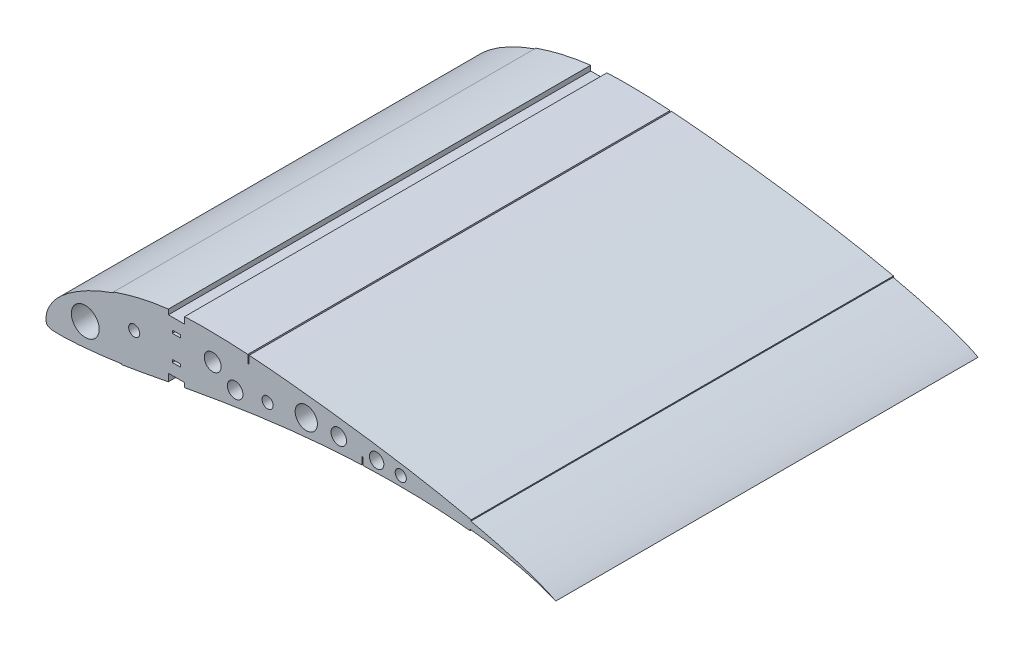
SolidWorks part; units mm, degrees
ref_plane "Front" through (0, 0, 0) normal (0, 0, 1) x (1, 0, 0)
ref_plane "Top" through (0, 0, 0) normal (0, 1, 0) x (1, 0, 0)
ref_plane "Right" through (0, 0, 0) normal (1, 0, 0) x (0, 0, -1)
curve "s1223bot"
  spline degree 3 poles (0.0013, 0.0452, 0) (0.0011, -0.0169, 0) (0.0007, -0.1295, 0) (0.0502, -0.2994, 0) (0.2271, -0.3838, 0) (0.4658, -0.3956, 0) (0.7919, -0.4071, 0) (1.2021, -0.3894, 0) (1.6917, -0.3569, 0) (2.2553, -0.3048, 0) (2.887, -0.2344, 0) (3.5838, -0.144, 0) (4.3454, -0.0178, 0) (5.1754, 0.1406, 0) (6.078, 0.3129, 0) (7.0488, 0.4949, 0) (8.0817, 0.6789, 0) (9.1691, 0.8581, 0) (10.3026, 1.0265, 0) (11.4724, 1.1779, 0) (12.668, 1.3079, 0) (13.8781, 1.4106, 0) (15.0905, 1.4835, 0) (16.2926, 1.5235, 0) (17.4713, 1.5286, 0) (18.6136, 1.4983, 0) (19.7062, 1.4334, 0) (20.7362, 1.3347, 0) (21.691, 1.2061, 0) (22.5587, 1.0511, 0) (23.3281, 0.8754, 0) (23.9878, 0.686, 0) (24.5221, 0.4881, 0) (24.9172, 0.2964, 0) (25.1776, 0.1426, 0) (25.3238, 0.0503, 0) (25.3852, 0.0098, 0) (25.4, 0, 0) knots 0 0 0 0 0.00721 0.013063 0.018988 0.028118 0.040671 0.056473 0.075356 0.097133 0.121591 0.148499 0.177977 0.210404 0.245731 0.28372 0.324063 0.36646 0.410535 0.455921 0.502185 0.548913 0.595655 0.641938 0.687301 0.731277 0.773403 0.813231 0.85031 0.884246 0.914623 0.941088 0.963171 0.980104 0.991535 0.99796 1 1 1 1
curve "s1223top"
  spline degree 3 poles (25.4, 0, 0) (25.3862, 0.0106, 0) (25.3348, 0.0499, 0) (25.2363, 0.1391, 0) (25.0929, 0.2743, 0) (24.903, 0.4317, 0) (24.6516, 0.5857, 0) (24.3364, 0.7365, 0) (23.9567, 0.8934, 0) (23.5122, 1.0548, 0) (23.0051, 1.2193, 0) (22.4381, 1.3857, 0) (21.8144, 1.5531, 0) (21.1374, 1.72, 0) (20.4109, 1.8852, 0) (19.6393, 2.0477, 0) (18.8274, 2.2065, 0) (17.9798, 2.3598, 0) (17.102, 2.5074, 0) (16.1989, 2.6472, 0) (15.2763, 2.7797, 0) (14.3403, 2.9038, 0) (13.3976, 3.019, 0) (12.4558, 3.1262, 0) (11.5225, 3.2227, 0) (10.6055, 3.3067, 0) (9.7111, 3.3734, 0) (8.8446, 3.4193, 0) (8.0106, 3.4391, 0) (7.2135, 3.437, 0) (6.4548, 3.3979, 0) (5.7342, 3.3188, 0) (5.0487, 3.207, 0) (4.3982, 3.0621, 0) (3.7833, 2.8923, 0) (3.2067, 2.7004, 0) (2.6707, 2.491, 0) (2.1788, 2.2652, 0) (1.7325, 2.0276, 0) (1.3343, 1.7809, 0) (0.9865, 1.5284, 0) (0.6894, 1.2755, 0) (0.4475, 1.0194, 0) (0.2611, 0.7624, 0) (0.125, 0.5124, 0) (0.0331, 0.275, 0) (0.0114, 0.1182, 0) (0.0013, 0.0452, 0) knots 0 0 0 0 0.001921 0.007154 0.014672 0.023714 0.034361 0.047156 0.062314 0.079753 0.099423 0.121231 0.145064 0.170804 0.198305 0.227412 0.257958 0.289755 0.322619 0.356355 0.390772 0.425638 0.460723 0.495752 0.530423 0.564432 0.59754 0.629553 0.660343 0.689741 0.717642 0.744276 0.769837 0.794379 0.817909 0.840322 0.861527 0.881481 0.900118 0.917382 0.933225 0.947578 0.96045 0.972074 0.982556 0.991876 1 1 1 1
ref_plane "Plane1" through (0, 0, 0) normal (0, 0, 1) x (1, 0, 0)
sketch "Sketch1" plane through (0, 0, 0) normal (0, 0, 1) x (1, 0, 0)
  line L0 (0.03, 1.0671) -> (599.47, 0) construction
  spline S2 degree 3 poles (0.03, 1.0671) (0.0255, -0.3992) (0.0173, -3.0557) (1.1853, -7.0667) (5.3593, -9.0582) (10.9923, -9.3375) (18.689, -9.6083) (28.3716, -9.1908) (39.9268, -8.4236) (53.2273, -7.1946) (68.1365, -5.5318) (84.582, -3.3994) (102.5555, -0.4191) (122.1448, 3.3182) (143.4476, 7.3855) (166.3598, 11.68) (190.7376, 16.0235) (216.4019, 20.2529) (243.1537, 24.227) (270.7622, 27.8) (298.9794, 30.8679) (327.5386, 33.293) (356.1532, 35.012) (384.5243, 35.9571) (412.3442, 36.0765) (439.3023, 35.362) (465.0901, 33.8306) (489.3978, 31.5015) (511.9341, 28.4655) (532.4122, 24.8063) (550.5712, 20.6608) (566.1399, 16.1904) (578.7504, 11.5186) (588.0748, 6.9961) (594.2214, 3.3662) (597.6712, 1.1861) (599.1206, 0.2303) (599.47, 0) knots 0 0 0 0 0.00721 0.013063 0.018988 0.028118 0.040671 0.056473 0.075356 0.097133 0.121591 0.148499 0.177977 0.210404 0.245731 0.28372 0.324063 0.36646 0.410535 0.455921 0.502185 0.548913 0.595655 0.641938 0.687301 0.731277 0.773403 0.813231 0.85031 0.884246 0.914623 0.941088 0.963171 0.980104 0.991535 0.99796 1 1 1 1
  spline S3 degree 3 poles (599.47, 0) (599.1444, 0.2495) (597.9316, 1.1785) (595.6059, 3.2827) (592.2219, 6.473) (587.7401, 10.189) (581.8079, 13.8236) (574.3676, 17.3833) (565.407, 21.0846) (554.9146, 24.8937) (542.9479, 28.7777) (529.5663, 32.7048) (514.8456, 36.6559) (498.8667, 40.5951) (481.7214, 44.4936) (463.5118, 48.3272) (444.3491, 52.0761) (424.3454, 55.6943) (403.6266, 59.1765) (382.3121, 62.4779) (360.5397, 65.605) (338.449, 68.533) (316.1999, 71.2524) (293.9704, 73.7827) (271.9445, 76.0598) (250.3016, 78.0413) (229.194, 79.6155) (208.7421, 80.6984) (189.0598, 81.166) (170.248, 81.1163) (152.3416, 80.1952) (135.3339, 78.3286) (119.1554, 75.6893) (103.8024, 72.2701) (89.2906, 68.2606) (75.6814, 63.7319) (63.0327, 58.7898) (51.4231, 53.4607) (40.8898, 47.853) (31.49, 42.0304) (23.2831, 36.0717) (16.2711, 30.1033) (10.5604, 24.0601) (6.1626, 17.9941) (2.9495, 12.0933) (0.782, 6.4892) (0.2689, 2.7899) (0.03, 1.0671) knots 0 0 0 0 0.001921 0.007154 0.014672 0.023714 0.034361 0.047156 0.062314 0.079753 0.099423 0.121231 0.145064 0.170804 0.198305 0.227412 0.257958 0.289755 0.322619 0.356355 0.390772 0.425638 0.460723 0.495752 0.530423 0.564432 0.59754 0.629553 0.660343 0.689741 0.717642 0.744276 0.769837 0.794379 0.817909 0.840322 0.861527 0.881481 0.900118 0.917382 0.933225 0.947578 0.96045 0.972074 0.982556 0.991876 1 1 1 1
  dimension "D1" = 599.44
extrude "Boss-Extrude1" add sketch "Sketch1" along normal blind 482.6
sketch "Sketch2" plane through (0, 0, 0) normal (0, 0, -1) x (-1, 0, 0)
  line L0 (0, 0) -> (-599.47, 0) construction
  line L1 (-149.86, 0) -> (-149.86, 151.2393) construction
  line L2 (-149.86, 44.2563) -> (-84.0346, 44.2563) construction
  line L3 (-149.86, 79.8163) -> (-80.7882, 79.8163) construction
  line L4 (-145.0975, 31.3975) -> (-145.0975, 28.2225)
  line L5 (-154.6225, 57.115) -> (-145.0975, 57.115)
  line L6 (-154.6225, 57.115) -> (-154.6225, 60.29)
  line L7 (-154.6225, 60.29) -> (-145.0975, 60.29)
  line L8 (-145.0975, 57.115) -> (-145.0975, 60.29)
  line L9 (-154.6225, 57.115) -> (-145.0975, 60.29) construction
  line L10 (-154.6225, 60.29) -> (-145.0975, 57.115) construction
  line L11 (-159.0675, 73.1488) -> (-140.6525, 73.1488)
  line L12 (-159.0675, 73.1488) -> (-159.0675, 89.0044)
  line L13 (-159.0675, 89.0044) -> (-140.6525, 89.0044)
  line L14 (-140.6525, 73.1488) -> (-140.6525, 89.0044)
  line L15 (-159.0675, 73.1488) -> (-140.6525, 89.0044) construction
  line L16 (-159.0675, 89.0044) -> (-140.6525, 73.1488) construction
  line L17 (-154.6225, 28.2225) -> (-145.0975, 28.2225)
  line L18 (-154.6225, 31.3975) -> (-154.6225, 28.2225)
  line L19 (-154.6225, 31.3975) -> (-145.0975, 31.3975)
  line L20 (-159.0675, -0.4918) -> (-140.6525, -0.4918)
  line L21 (-140.6525, 15.3638) -> (-140.6525, -0.4918)
  line L22 (-159.0675, 15.3638) -> (-140.6525, 15.3638)
  line L23 (-159.0675, 15.3638) -> (-159.0675, -0.4918)
  line L25 (-231.3937, 96.4856) -> (-232.9812, 96.4856)
  line L26 (-231.3937, 96.4856) -> (-231.3937, 70.3014)
  line L27 (-231.3937, 70.3014) -> (-232.9812, 70.3014)
  line L28 (-232.9812, 96.4856) -> (-232.9812, 70.3014)
  line L29 (-231.3937, 96.4856) -> (-232.9812, 70.3014) construction
  line L31 (-361.6917, 26.0584) -> (-363.2792, 26.0584)
  line L32 (-361.6917, 26.0584) -> (-361.6917, 43.6863)
  line L33 (-361.6917, 43.6863) -> (-363.2792, 43.6863)
  line L34 (-363.2792, 26.0584) -> (-363.2792, 43.6863)
  line L35 (-361.6917, 26.0584) -> (-363.2792, 43.6863) construction
  line L36 (-361.6917, 43.6863) -> (-363.2792, 26.0584) construction
  circle A2 centre (-45.7138, 19.2098) radius 15.9068
  spline S0 degree 3 poles (-599.47, 0) (-599.1444, 0.2495) (-597.9316, 1.1785) (-595.6059, 3.2827) (-592.2219, 6.473) (-587.7401, 10.189) (-581.8079, 13.8236) (-574.3676, 17.3833) (-565.407, 21.0846) (-554.9146, 24.8937) (-542.9479, 28.7777) (-529.5663, 32.7048) (-514.8456, 36.6559) (-498.8667, 40.5951) (-481.7214, 44.4936) (-463.5118, 48.3272) (-444.3491, 52.0761) (-424.3454, 55.6943) (-403.6266, 59.1765) (-382.3121, 62.4779) (-360.5397, 65.605) (-338.449, 68.533) (-316.1999, 71.2524) (-293.9704, 73.7827) (-271.9445, 76.0598) (-250.3016, 78.0413) (-229.194, 79.6155) (-208.7421, 80.6984) (-189.0598, 81.166) (-170.248, 81.1163) (-152.3416, 80.1952) (-135.3339, 78.3286) (-119.1554, 75.6893) (-103.8024, 72.2701) (-89.2906, 68.2606) (-75.6814, 63.7319) (-63.0327, 58.7898) (-51.4231, 53.4607) (-40.8898, 47.853) (-31.49, 42.0304) (-23.2831, 36.0717) (-16.2711, 30.1033) (-10.5604, 24.0601) (-6.1626, 17.9941) (-2.9495, 12.0933) (-0.782, 6.4892) (-0.2689, 2.7899) (-0.03, 1.0671) knots 0 0 0 0 0.001921 0.007154 0.014672 0.023714 0.034361 0.047156 0.062314 0.079753 0.099423 0.121231 0.145064 0.170804 0.198305 0.227412 0.257958 0.289755 0.322619 0.356355 0.390772 0.425638 0.460723 0.495752 0.530423 0.564432 0.59754 0.629553 0.660343 0.689741 0.717642 0.744276 0.769837 0.794379 0.817909 0.840322 0.861527 0.881481 0.900118 0.917382 0.933225 0.947578 0.96045 0.972074 0.982556 0.991876 1 1 1 1 construction
  point P7 (-149.86, 58.7025)
  point P17 (-149.86, 81.0766)
  point P39 (-362.4855, 34.8724)
  dimension "D8" = 31.8135
  dimension "D1" = 149.86
  dimension "D2" = 35.56
  dimension "D3" = 14.4462
  dimension "D4" = 9.525
  dimension "D5" = 3.175
  dimension "D6" = 18.415
  dimension "D7" = 28.8925
  dimension "D10" = 1.5875
  dimension "D11" = 1.5875
extrude "Cut-Extrude1" cut sketch "Sketch2" against normal through all
sketch "Sketch3" plane through (0, 0, 482.6) normal (0, 0, 1) x (1, 0, 0)
  line L0 (77.9334, 64.4077) -> (87.0074, -2.931) construction
  line L1 (77.9334, 64.4077) -> (78.1966, 63.6589)
  line L2 (87.0074, -2.931) -> (86.8874, -2.1464)
  line L3 (486.6728, 43.3483) -> (485.4189, 31.7937) construction
  line L4 (485.4189, 31.7937) -> (485.5901, 33.372)
  line L5 (486.6728, 43.3483) -> (486.3262, 41.799)
  spline S0 degree 3 poles (-1970.3924, 338.6511) (98.8632, 45.6756) (-8.8415, 27.3664) (1.1853, -7.0667) (5.3593, -9.0582) (10.9923, -9.3375) (18.689, -9.6083) (28.3716, -9.1908) (39.9268, -8.4236) (53.2273, -7.1946) (68.1365, -5.5318) (84.582, -3.3994) (102.5555, -0.4191) (473.5396, 70.358) (838.1335, 141.3605) (1502.5551, -1332.6043) knots -0.144018 -0.144018 -0.144018 -0.144018 0.00721 0.013063 0.018988 0.028118 0.040671 0.056473 0.075356 0.097133 0.121591 0.148499 0.177977 0.210404 1.989908 1.989908 1.989908 1.989908 only from (0.03, 1.0671) to (140.6525, 6.8433) construction
  spline S1 degree 3 poles (277.129, -1844.3223) (714.082, -186.0597) (395.3013, 120.739) (119.1554, 75.6893) (103.8024, 72.2701) (89.2906, 68.2606) (75.6814, 63.7319) (63.0327, 58.7898) (51.4231, 53.4607) (40.8898, 47.853) (31.49, 42.0304) (23.2831, 36.0717) (16.2711, 30.1033) (10.5604, 24.0601) (6.1626, 17.9941) (2.9495, 12.0933) (-13.1155, -29.4414) (78.3319, -94.0823) (-1968.3105, 348.48) knots -0.515421 -0.515421 -0.515421 -0.515421 0.744276 0.769837 0.794379 0.817909 0.840322 0.861527 0.881481 0.900118 0.917382 0.933225 0.947578 0.96045 0.972074 0.982556 0.991876 1.179048 1.179048 1.179048 1.179048 only from (140.6525, 78.86) to (0.03, 1.0671) construction
  spline S2 degree 3 poles (0.03, 1.0671) (0.0255, -0.3992) (0.0173, -3.0557) (1.1853, -7.0667) (5.3593, -9.0582) (10.9923, -9.3375) (18.689, -9.6083) (28.3716, -9.1908) (39.9268, -8.4236) (53.2273, -7.1946) (68.1365, -5.5318) (79.5756, -4.0486) (86.0206, -3.0819) (87.0074, -2.931) knots 0 0 0 0 0.00721 0.013063 0.018988 0.028118 0.040671 0.056473 0.075356 0.097133 0.121591 0.148499 0.153366 0.153366 0.153366 0.153366
  spline S3 degree 3 poles (77.9334, 64.4077) (77.114, 64.1196) (72.0313, 62.3057) (63.0327, 58.7898) (51.4231, 53.4607) (40.8898, 47.853) (31.49, 42.0304) (23.2831, 36.0717) (16.2711, 30.1033) (10.5604, 24.0601) (6.1626, 17.9941) (2.9495, 12.0933) (0.782, 6.4892) (0.2689, 2.7899) (0.03, 1.0671) knots 0.836254 0.836254 0.836254 0.836254 0.840322 0.861527 0.881481 0.900118 0.917382 0.933225 0.947578 0.96045 0.972074 0.982556 0.991876 1 1 1 1
  spline S4 degree 1 poles (78.1966, 63.6589) (0.8236, 1.0111) knots 0 0 1 1 construction
  spline S5 degree 1 poles (0.8236, 1.0111) (86.8874, -2.1464) knots 0 0 1 1 construction
  spline S6 degree 3 poles (78.1966, 63.6589) (69.9856, 60.7723) (57.8565, 55.8468) (42.3943, 47.8342) (31.2745, 41.0045) (22.5488, 34.51) (16.0869, 28.7338) (11.6338, 24.0169) (7.7076, 18.8608) (4.9669, 14.2264) (3.1357, 10.321) (1.9971, 7.3155) (1.2705, 4.2499) (0.9722, 2.0827) (0.8236, 1.0111) knots 0.836254 0.836254 0.836254 0.836254 0.87717 0.897628 0.918086 0.938543 0.948772 0.959001 0.96923 0.979459 0.984573 0.989688 0.994802 0.999917 0.999917 0.999917 0.999917
  spline S7 degree 3 poles (0.8236, 1.0111) (0.8221, 0.5289) (0.8199, -0.4416) (0.8716, -1.8611) (1.0281, -3.2766) (1.3362, -4.6703) (1.8567, -5.8585) (2.8808, -6.9975) (5.0911, -7.9582) (7.8516, -8.3986) (11.7354, -8.5583) (16.6431, -8.7442) (22.4904, -8.6592) (28.3666, -8.3658) (34.2408, -8.0058) (40.109, -7.5703) (45.9731, -7.0649) (53.7874, -6.3127) (63.5446, -5.2532) (75.2379, -3.8289) (83.0086, -2.7395) (86.8874, -2.1464) knots 0.000088 0.000088 0.000088 0.000088 0.002483 0.004878 0.007273 0.009668 0.012063 0.014458 0.019248 0.024037 0.028827 0.038407 0.047987 0.057567 0.067147 0.076727 0.086307 0.095887 0.115046 0.134206 0.153366 0.153366 0.153366 0.153366
  spline S8 degree 3 poles (-583.8836, 1359.92) (-752.4483, -493.2907) (-179.6719, 33.5361) (412.3442, 36.0765) (439.3023, 35.362) (465.0901, 33.8306) (489.3978, 31.5015) (511.9341, 28.4655) (532.4122, 24.8063) (550.5712, 20.6608) (566.1399, 16.1904) (578.7504, 11.5186) (588.0748, 6.9961) (594.2214, 3.3662) (633.3139, -21.3389) (658.727, -62.7912) (1792.2745, 1603.3571) knots -2.154817 -2.154817 -2.154817 -2.154817 0.641938 0.687301 0.731277 0.773403 0.813231 0.85031 0.884246 0.914623 0.941088 0.963171 0.980104 0.991535 0.99796 1.205564 1.205564 1.205564 1.205564 only from (363.2792, 35.1934) to (599.47, 0) construction
  spline S9 degree 3 poles (-603.0561, -1596.942) (659.4194, -4.3542) (616.3736, -15.5063) (595.6059, 3.2827) (592.2219, 6.473) (587.7401, 10.189) (581.8079, 13.8236) (574.3676, 17.3833) (565.407, 21.0846) (554.9146, 24.8937) (542.9479, 28.7777) (529.5663, 32.7048) (514.8456, 36.6559) (498.8667, 40.5951) (481.7214, 44.4936) (463.5118, 48.3272) (444.3491, 52.0761) (424.3454, 55.6943) (403.6266, 59.1765) (382.3121, 62.4779) (360.5397, 65.605) (338.449, 68.533) (316.1999, 71.2524) (293.9704, 73.7827) (271.9445, 76.0598) (-43.152, 104.9077) (-360.3028, 21.1709) (-697.8307, -1621.5504) knots -0.116345 -0.116345 -0.116345 -0.116345 0.001921 0.007154 0.014672 0.023714 0.034361 0.047156 0.062314 0.079753 0.099423 0.121231 0.145064 0.170804 0.198305 0.227412 0.257958 0.289755 0.322619 0.356355 0.390772 0.425638 0.460723 0.495752 0.530423 0.564432 1.97767 1.97767 1.97767 1.97767 only from (599.47, 0) to (232.9812, 79.2914) construction
  spline S10 degree 3 poles (485.4189, 31.7937) (486.9268, 31.6301) (495.992, 30.6132) (511.9341, 28.4655) (532.4122, 24.8063) (550.5712, 20.6608) (566.1399, 16.1904) (578.7504, 11.5186) (588.0748, 6.9961) (594.2214, 3.3662) (597.6712, 1.1861) (599.1206, 0.2303) (599.47, 0) knots 0.805836 0.805836 0.805836 0.805836 0.813231 0.85031 0.884246 0.914623 0.941088 0.963171 0.980104 0.991535 0.99796 1 1 1 1
  spline S11 degree 3 poles (599.47, 0) (599.1444, 0.2495) (597.9316, 1.1785) (595.6059, 3.2827) (592.2219, 6.473) (587.7401, 10.189) (581.8079, 13.8236) (574.3676, 17.3833) (565.407, 21.0846) (554.9146, 24.8937) (542.9479, 28.7777) (529.5663, 32.7048) (514.8456, 36.6559) (500.4005, 40.2169) (490.8614, 42.4112) (486.6728, 43.3483) knots 0 0 0 0 0.001921 0.007154 0.014672 0.023714 0.034361 0.047156 0.062314 0.079753 0.099423 0.121231 0.145064 0.170804 0.190907 0.190907 0.190907 0.190907
  spline S12 degree 1 poles (485.5901, 33.372) (583.1822, 11.0728) knots 0 0 1 1 construction
  spline S13 degree 1 poles (583.1822, 11.0728) (486.3262, 41.799) knots 0 0 1 1 construction
  spline S14 degree 3 poles (485.5901, 33.372) (493.8935, 32.4709) (510.4647, 30.3452) (535.1597, 25.9552) (555.5166, 21.0696) (571.5171, 15.9958) (579.3626, 12.8503) (583.1822, 11.0728) knots 0.805836 0.805836 0.805836 0.805836 0.846447 0.887057 0.927667 0.947973 0.968278 0.968278 0.968278 0.968278
  spline S15 degree 3 poles (583.1822, 11.0728) (581.384, 12.138) (577.6909, 14.0735) (569.9778, 17.5456) (560.1087, 21.3994) (548.0427, 25.5066) (531.7785, 30.4886) (511.2225, 36.0214) (494.6384, 39.9396) (486.3262, 41.799) knots 0.031057 0.031057 0.031057 0.031057 0.041047 0.051038 0.071019 0.091001 0.110982 0.150944 0.190907 0.190907 0.190907 0.190907
  dimension "D1" = 0.7937
  dimension "D2" = 1.5875
extrude "Cut-Extrude2" cut sketch "Sketch3" against normal through all
sketch "Sketch4" plane through (0, 0, 482.6) normal (0, 0, 1) x (1, 0, 0)
  circle A0 centre (101.6, 38.1) radius 6.35
  circle A1 centre (254, 43.18) radius 6.35
  dimension "D3" = 12.7
  dimension "D5" = 12.7
  dimension "D1" = 101.6
  dimension "D2" = 38.1
  dimension "D4" = 254
  dimension "D6" = 43.18
extrude "Cut-Extrude3" cut sketch "Sketch4" against normal blind 254
sketch "Sketch5" plane through (0, 0, 482.6) normal (0, 0, 1) x (1, 0, 0)
  circle A0 centre (191.3236, 51.8111) radius 9.652
  dimension "D1" = 19.304
  dimension "D2" = 190.5
  dimension "D3" = 50.8
extrude "Cut-Extrude4" cut sketch "Sketch5" against normal through all
sketch "Sketch6" plane through (0, 0, 482.6) normal (0, 0, 1) x (1, 0, 0)
  circle A0 centre (298.2287, 50.0531) radius 12.7
  circle A1 centre (335.3501, 50.0531) radius 8.89
  circle A2 centre (406.2028, 46.9058) radius 6.35
  circle A3 centre (378.6031, 48.118) radius 8.255
  circle A4 centre (216.9775, 36.9305) radius 8.89
  point P6 (220.0549, 40.5555)
  point P7 (213.9993, 37.2182)
  point P12 (0, 0)
  point P13 (216.9775, 36.9305)
extrude "Cut-Extrude5" cut sketch "Sketch6" against normal up to surface (482.6 mm away) up to face at (200.9756, 51.8111, 0)
